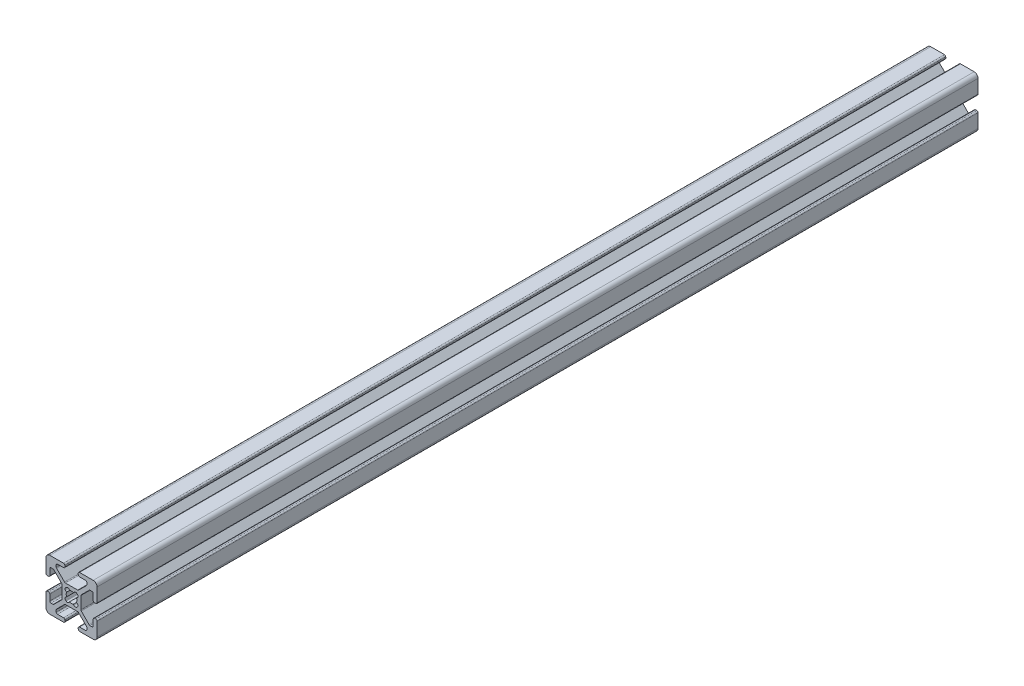
SolidWorks part; units mm, degrees
material "6105-T5 Aluminum"
ref_plane "Front Plane" through (0, 0, 0) normal (0, 0, 1) x (1, 0, 0)
ref_plane "Top Plane" through (0, 0, 0) normal (0, 1, 0) x (1, 0, 0)
ref_plane "Right Plane" through (0, 0, 0) normal (1, 0, 0) x (0, 0, -1)
sketch "Sketch1" plane through (0, 0, 0) normal (0, 0, 1) x (1, 0, 0)
  line L0 (9.492, 2.63) -> (9.008, 2.63)
  line L1 (8.5, 3.138) -> (8.5, 5.487)
  line L2 (10, 3.138) -> (10, 8.5)
  line L3 (3.655, -2.3839) -> (3.655, 2.3839)
  line L4 (7.2661, 5.995) -> (7.992, 5.995)
  line L5 (6.9069, 5.8462) -> (3.8038, 2.7431)
  line L6 (9.492, -2.63) -> (9.008, -2.63)
  line L7 (10, -3.138) -> (10, -8.5)
  line L8 (8.5, -3.138) -> (8.5, -5.487)
  line L9 (7.2661, -5.995) -> (7.992, -5.995)
  line L10 (6.9069, -5.8462) -> (3.8038, -2.7431)
  line L11 (2.1249, -2.3045) -> (2.3045, -2.1249)
  line L12 (-2.63, 9.492) -> (-2.63, 9.008)
  line L13 (-3.138, 10) -> (-8.5, 10)
  line L14 (-3.138, 8.5) -> (-5.487, 8.5)
  line L15 (2.3839, 3.655) -> (-2.3839, 3.655)
  line L16 (-5.995, 7.2661) -> (-5.995, 7.992)
  line L17 (-5.8462, 6.9069) -> (-2.7431, 3.8038)
  line L18 (2.63, 9.492) -> (2.63, 9.008)
  line L19 (3.138, 10) -> (8.5, 10)
  line L20 (3.138, 8.5) -> (5.487, 8.5)
  line L21 (5.995, 7.2661) -> (5.995, 7.992)
  line L22 (5.8462, 6.9069) -> (2.7431, 3.8038)
  line L23 (2.3045, 2.1249) -> (2.1249, 2.3045)
  line L24 (-9.492, -2.63) -> (-9.008, -2.63)
  line L25 (-10, -3.138) -> (-10, -8.5)
  line L26 (-8.5, -3.138) -> (-8.5, -5.487)
  line L27 (-3.655, 2.3839) -> (-3.655, -2.3839)
  line L28 (-7.2661, -5.995) -> (-7.992, -5.995)
  line L29 (-6.9069, -5.8462) -> (-3.8038, -2.7431)
  line L30 (-9.492, 2.63) -> (-9.008, 2.63)
  line L31 (-10, 3.138) -> (-10, 8.5)
  line L32 (-8.5, 3.138) -> (-8.5, 5.487)
  line L33 (-7.2661, 5.995) -> (-7.992, 5.995)
  line L34 (-6.9069, 5.8462) -> (-3.8038, 2.7431)
  line L35 (-2.1249, 2.3045) -> (-2.3045, 2.1249)
  line L36 (2.63, -9.492) -> (2.63, -9.008)
  line L37 (3.138, -10) -> (8.5, -10)
  line L38 (3.138, -8.5) -> (5.487, -8.5)
  line L39 (-2.3839, -3.655) -> (2.3839, -3.655)
  line L40 (5.995, -7.2661) -> (5.995, -7.992)
  line L41 (5.8462, -6.9069) -> (2.7431, -3.8038)
  line L42 (-2.63, -9.492) -> (-2.63, -9.008)
  line L43 (-3.138, -10) -> (-8.5, -10)
  line L44 (-3.138, -8.5) -> (-5.487, -8.5)
  line L45 (-5.995, -7.2661) -> (-5.995, -7.992)
  line L46 (-5.8462, -6.9069) -> (-2.7431, -3.8038)
  line L47 (-2.3045, -2.1249) -> (-2.1249, -2.3045)
  arc A0 (-0.804, -1.9351) -> (0.804, -1.9351) centre (0, 0) ccw
  arc A1 (8.5, 5.487) -> (7.992, 5.995) centre (7.992, 5.487) ccw
  arc A2 (7.2661, 5.995) -> (6.9069, 5.8462) centre (7.2661, 5.487) ccw
  arc A3 (3.8038, 2.7431) -> (3.655, 2.3839) centre (4.163, 2.3839) ccw
  arc A4 (3.655, -2.3839) -> (3.8038, -2.7431) centre (4.163, -2.3839) ccw
  arc A5 (6.9069, -5.8462) -> (7.2661, -5.995) centre (7.2661, -5.487) ccw
  arc A6 (7.992, -5.995) -> (8.5, -5.487) centre (7.992, -5.487) ccw
  arc A7 (9.008, -2.63) -> (8.5, -3.138) centre (9.008, -3.138) ccw
  arc A8 (10, -3.138) -> (9.492, -2.63) centre (9.492, -3.138) ccw
  arc A9 (9.492, 2.63) -> (10, 3.138) centre (9.492, 3.138) ccw
  arc A10 (8.5, 3.138) -> (9.008, 2.63) centre (9.008, 3.138) ccw
  arc A11 (0.804, -1.9351) -> (2.1249, -2.3045) centre (1.5684, -1.748) ccw
  arc A12 (2.3045, -2.1249) -> (1.9351, -0.804) centre (1.748, -1.5684) ccw
  arc A13 (-2.63, 9.492) -> (-3.138, 10) centre (-3.138, 9.492) ccw
  arc A14 (-3.138, 8.5) -> (-2.63, 9.008) centre (-3.138, 9.008) ccw
  arc A15 (1.9351, -0.804) -> (1.9351, 0.804) centre (0, 0) ccw
  arc A16 (-2.7431, 3.8038) -> (-2.3839, 3.655) centre (-2.3839, 4.163) ccw
  arc A17 (-5.487, 8.5) -> (-5.995, 7.992) centre (-5.487, 7.992) ccw
  arc A18 (-5.995, 7.2661) -> (-5.8462, 6.9069) centre (-5.487, 7.2661) ccw
  arc A19 (2.63, 9.008) -> (3.138, 8.5) centre (3.138, 9.008) ccw
  arc A20 (3.138, 10) -> (2.63, 9.492) centre (3.138, 9.492) ccw
  arc A21 (5.995, 7.992) -> (5.487, 8.5) centre (5.487, 7.992) ccw
  arc A22 (5.8462, 6.9069) -> (5.995, 7.2661) centre (5.487, 7.2661) ccw
  arc A23 (2.3839, 3.655) -> (2.7431, 3.8038) centre (2.3839, 4.163) ccw
  arc A24 (1.9351, 0.804) -> (2.3045, 2.1249) centre (1.748, 1.5684) ccw
  arc A25 (2.1249, 2.3045) -> (0.804, 1.9351) centre (1.5684, 1.748) ccw
  arc A26 (-9.492, -2.63) -> (-10, -3.138) centre (-9.492, -3.138) ccw
  arc A27 (-8.5, -3.138) -> (-9.008, -2.63) centre (-9.008, -3.138) ccw
  arc A28 (0.804, 1.9351) -> (-0.804, 1.9351) centre (0, 0) ccw
  arc A29 (-3.8038, -2.7431) -> (-3.655, -2.3839) centre (-4.163, -2.3839) ccw
  arc A30 (-8.5, -5.487) -> (-7.992, -5.995) centre (-7.992, -5.487) ccw
  arc A31 (-7.2661, -5.995) -> (-6.9069, -5.8462) centre (-7.2661, -5.487) ccw
  arc A32 (-9.008, 2.63) -> (-8.5, 3.138) centre (-9.008, 3.138) ccw
  arc A33 (-10, 3.138) -> (-9.492, 2.63) centre (-9.492, 3.138) ccw
  arc A34 (-7.992, 5.995) -> (-8.5, 5.487) centre (-7.992, 5.487) ccw
  arc A35 (-6.9069, 5.8462) -> (-7.2661, 5.995) centre (-7.2661, 5.487) ccw
  arc A36 (-3.655, 2.3839) -> (-3.8038, 2.7431) centre (-4.163, 2.3839) ccw
  arc A37 (-0.804, 1.9351) -> (-2.1249, 2.3045) centre (-1.5684, 1.748) ccw
  arc A38 (-2.3045, 2.1249) -> (-1.9351, 0.804) centre (-1.748, 1.5684) ccw
  arc A39 (2.63, -9.492) -> (3.138, -10) centre (3.138, -9.492) ccw
  arc A40 (3.138, -8.5) -> (2.63, -9.008) centre (3.138, -9.008) ccw
  arc A41 (-1.9351, 0.804) -> (-1.9351, -0.804) centre (0, 0) ccw
  arc A42 (2.7431, -3.8038) -> (2.3839, -3.655) centre (2.3839, -4.163) ccw
  arc A43 (5.487, -8.5) -> (5.995, -7.992) centre (5.487, -7.992) ccw
  arc A44 (5.995, -7.2661) -> (5.8462, -6.9069) centre (5.487, -7.2661) ccw
  arc A45 (-2.63, -9.008) -> (-3.138, -8.5) centre (-3.138, -9.008) ccw
  arc A46 (-3.138, -10) -> (-2.63, -9.492) centre (-3.138, -9.492) ccw
  arc A47 (-5.995, -7.992) -> (-5.487, -8.5) centre (-5.487, -7.992) ccw
  arc A48 (-5.8462, -6.9069) -> (-5.995, -7.2661) centre (-5.487, -7.2661) ccw
  arc A49 (-2.3839, -3.655) -> (-2.7431, -3.8038) centre (-2.3839, -4.163) ccw
  arc A50 (-1.9351, -0.804) -> (-2.3045, -2.1249) centre (-1.748, -1.5684) ccw
  arc A51 (-2.1249, -2.3045) -> (-0.804, -1.9351) centre (-1.5684, -1.748) ccw
  arc A52 (10, 8.5) -> (8.5, 10) centre (8.5, 8.5) ccw
  arc A53 (8.5, -10) -> (10, -8.5) centre (8.5, -8.5) ccw
  arc A54 (-10, -8.5) -> (-8.5, -10) centre (-8.5, -8.5) ccw
  arc A55 (-8.5, 10) -> (-10, 8.5) centre (-8.5, 8.5) ccw
extrude "Extrude1" add sketch "Sketch1" against normal blind 345
